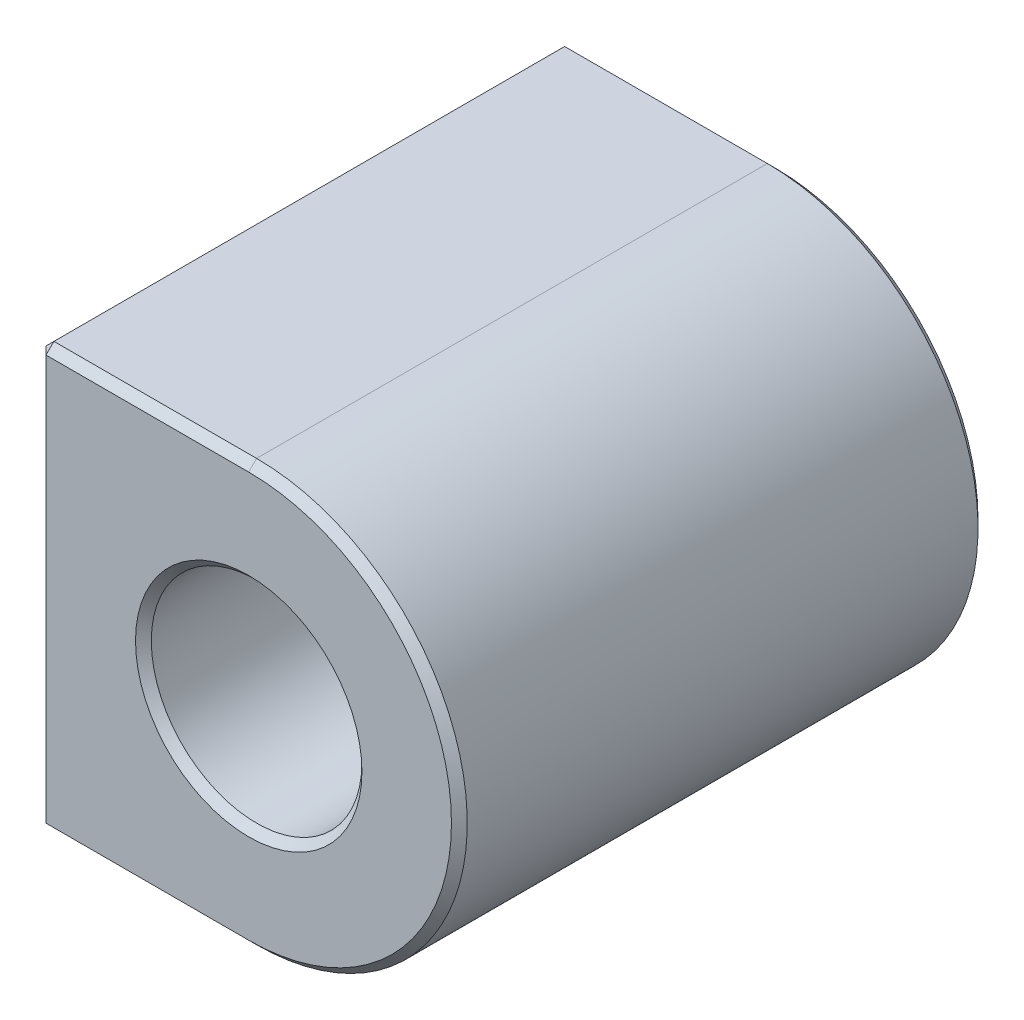
SolidWorks part; units mm, degrees
ref_plane "Front Plane" through (0, 0, 0) normal (0, 0, 1) x (1, 0, 0)
ref_plane "Top Plane" through (0, 0, 0) normal (0, 1, 0) x (1, 0, 0)
ref_plane "Right Plane" through (0, 0, 0) normal (1, 0, 0) x (0, 0, -1)
sketch "Sketch1" plane through (0, 0, 0) normal (0, 0, 1) x (1, 0, 0)
  line L1 (0, 4) -> (-4, 4)
  line L3 (0, -4) -> (-4, -4)
  line L4 (-4, 4) -> (-4, -4)
  arc A0 (0, -4) -> (0, 4) centre (0, 0) ccw
  circle A1 centre (0, 0) radius 2
  dimension "D1" = 8
  dimension "D3" = 4
  dimension "D2" = 4
extrude "Boss-Extrude1" add sketch "Sketch1" along normal mid plane 10
chamfer "Chamfer1" distance 0.15 angle 45 12 edges at (2, 0, 5) (2, 0, -5) (4, 0, 5) (4, 0, -5) (-2, -4, 5) (-2, -4, -5) (-2, 4, 5) (-2, 4, -5) (-4, 4, 0) (-4, 0, 5) (-4, -4, 0) (-4, 0, -5)
